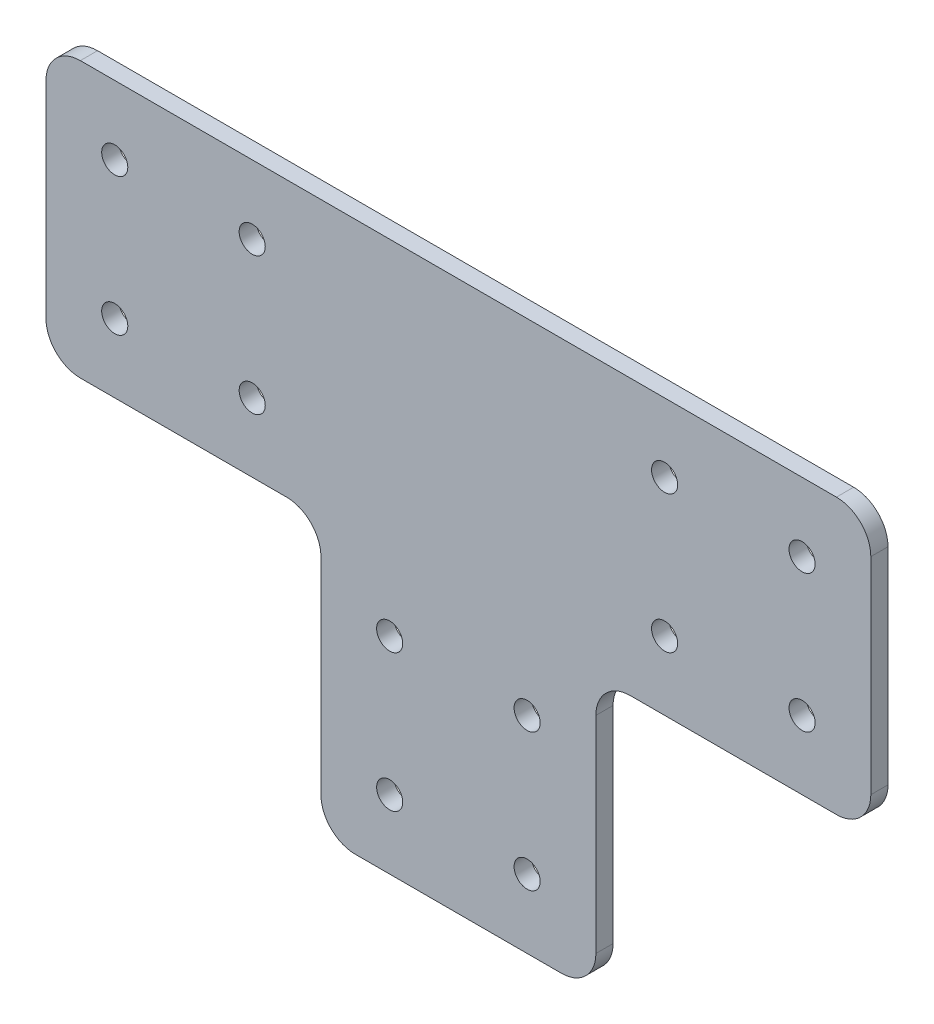
SolidWorks part; units mm, degrees
material "6061-T6 (SS)"
ref_plane "Front Plane" through (0, 0, 0) normal (0, 0, 1) x (1, 0, 0)
ref_plane "Top Plane" through (0, 0, 0) normal (0, 1, 0) x (1, 0, 0)
ref_plane "Right Plane" through (0, 0, 0) normal (1, 0, 0) x (0, 0, -1)
sketch "Sketch1" plane through (0, 0, 0) normal (0, 0, 1) x (1, 0, 0)
  line L0 (-76.2, 0) -> (76.2, 0)
  line L1 (76.2, 0) -> (76.2, -50.8)
  line L2 (76.2, -50.8) -> (25.4, -50.8)
  line L3 (25.4, -50.8) -> (25.4, -101.6)
  line L4 (25.4, -101.6) -> (-25.4, -101.6)
  line L5 (-25.4, -101.6) -> (-25.4, -50.8)
  line L6 (-25.4, -50.8) -> (-76.2, -50.8)
  line L7 (-76.2, -50.8) -> (-76.2, 0)
  line L8 (0, 0) -> (0, -50000) construction
  circle A0 centre (-63.5, -12.7) radius 2.413
  circle A1 centre (-63.5, -38.1) radius 2.413
  circle A2 centre (-38.1, -12.7) radius 2.413
  circle A3 centre (-38.1, -38.1) radius 2.413
  circle A4 centre (-12.7, -88.9) radius 2.413
  circle A5 centre (-12.7, -63.5) radius 2.413
  circle A6 centre (12.7, -88.9) radius 2.413
  circle A7 centre (12.7, -63.5) radius 2.413
  circle A8 centre (63.5, -38.1) radius 2.413
  circle A9 centre (38.1, -38.1) radius 2.413
  circle A10 centre (38.1, -12.7) radius 2.413
  circle A11 centre (63.5, -12.7) radius 2.413
  point P4 (0, 0)
  point P10 (0, -101.6)
  dimension "D5" = 4.826
  dimension "D6" = 12.7
  dimension "D7" = 25.4
  dimension "D8" = 25.4
  dimension "D9" = 25.4
  dimension "D10" = 12.7
  dimension "D11" = 12.7
  dimension "D12" = 12.7
  dimension "D1" = 50.8
  dimension "D2" = 50.8
  dimension "D3" = 50.8
  dimension "D4" = 50.8
extrude "Boss-Extrude1" add sketch "Sketch1" along normal blind 3.175
fillet "Fillet1" radius 6.35 8 edges at (25.4, -101.6, 1.5875) (-25.4, -101.6, 1.5875) (-25.4, -50.8, 1.5875) (-76.2, -50.8, 1.5875) (76.2, 0, 1.5875) (76.2, -50.8, 1.5875) (25.4, -50.8, 1.5875) (-76.2, 0, 1.5875)
